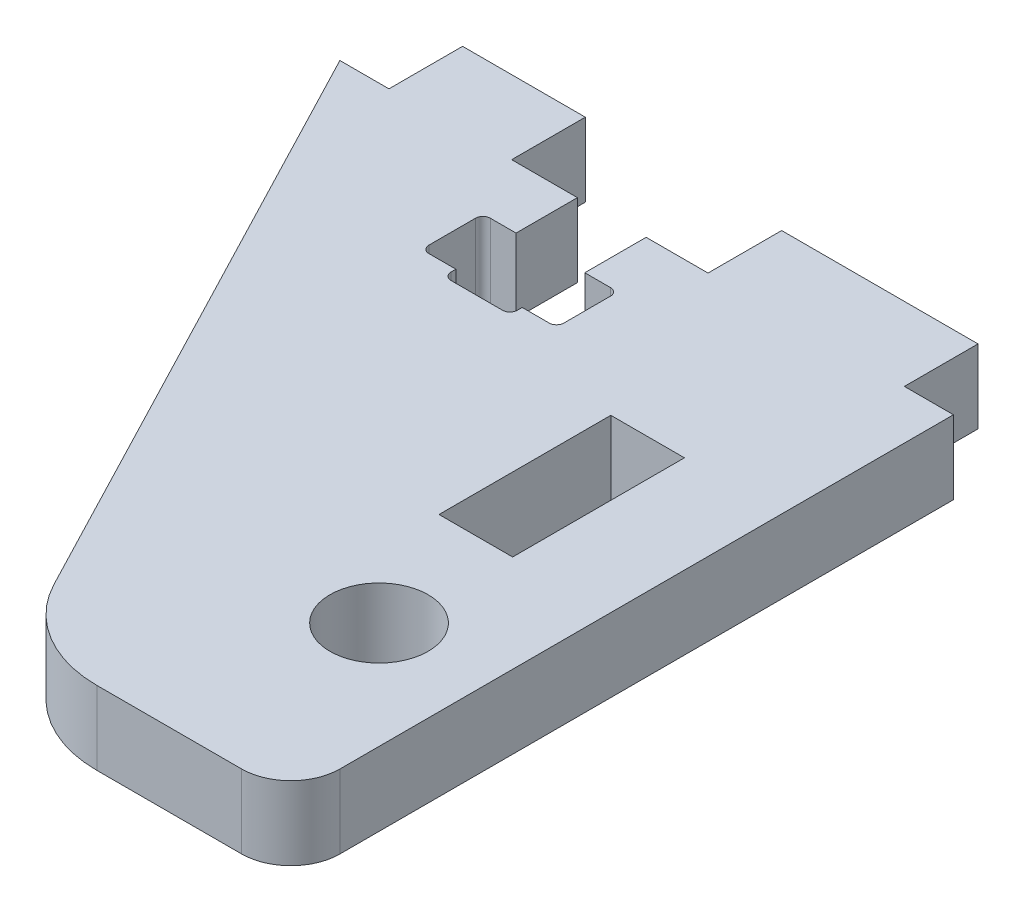
SolidWorks part; units mm, degrees
ref_plane "前视基准面" through (0, 0, 0) normal (0, 0, 1) x (1, 0, 0)
ref_plane "上视基准面" through (0, 0, 0) normal (0, 1, 0) x (1, 0, 0)
ref_plane "右视基准面" through (0, 0, 0) normal (1, 0, 0) x (0, 0, -1)
sketch "草图1" plane through (0, 0, 0) normal (0, 0, 1) x (1, 0, 0)
  line L0 (0, 0) -> (25, 0)
  line L4 (25, 0) -> (25, 5)
  line L5 (25, 5) -> (0, 5)
  line L6 (0, 5) -> (0, 0)
extrude "凸台-拉伸1" add sketch "草图1" along normal blind 24
sketch "草图2" plane through (0, 0, 0) normal (0, 0, -1) x (-1, 0, 0)
  line L0 (0, 5) -> (-2, 5)
  line L1 (-2, 5) -> (-2, 0)
  line L2 (-2, 5) -> (-7, 5)
  line L3 (-7, 5) -> (-7, 0)
  line L4 (0, 0) -> (0, 5)
  line L5 (0, 5) -> (-25, 5)
  line L6 (-25, 5) -> (-25, 0)
  line L7 (-25, 0) -> (0, 0)
  line L8 (0, 0) -> (0, 5)
  line L9 (0, 5) -> (-25, 5)
  line L10 (-25, 5) -> (-25, 0)
  line L11 (-25, 0) -> (0, 0)
  line L12 (-25, 5) -> (-23, 5)
  line L13 (-23, 5) -> (-23, 0)
  line L14 (-23, 5) -> (-15, 5)
  line L15 (-15, 5) -> (-15, 0)
  line M6 (0, 5) -> (-25, 5)
  line M8 (-25, 0) -> (0, 0)
  dimension "D1" = 0
extrude "凸台-拉伸2" add sketch "草图2" along normal blind 3 contours L3 L1 M6 M8 | L15 L9 L13 L11
sketch "草图3" plane through (0, 0, 0) normal (0, -1, 0) x (1, 0, 0)
  line L0 (0, 24) -> (25, 24) construction
  line L1 (0, 24) -> (25, 24)
  line L2 (0, 24) -> (0, 0) construction
  line L3 (0, 24) -> (0, 0)
  line L4 (0, 0) -> (12.5, 24)
  line M12 (0, 24) -> (0, 0)
extrude "切除-拉伸2" cut sketch "草图3" against normal blind 5 contours L4 L1 M12
sketch "草图4" plane through (0, 0, 0) normal (0, -1, 0) x (1, 0, 0)
  line L0 (12.5, 24) -> (25, 24) construction
  line L1 (12.5, 24) -> (25, 24)
  line L2 (25, 24) -> (25, 27)
  line L3 (25, 27) -> (14.0625, 27)
  line L4 (12.5, 24) -> (14.0625, 27)
extrude "凸台-拉伸3" add sketch "草图4" against normal up to surface (5 mm away) up to face at (13.0417, 5, 3)
fillet "圆角1" radius 5 1 edges at (14.0625, 2.5, 27)
fillet "圆角2" radius 2 1 edges at (25, 2.5, 27)
sketch "草图7" plane through (0, 5, 0) normal (0, 1, 0) x (1, 0, 0)
  line L12 (17.0959, -27) -> (23, -27)
  line L13 (25, -25) -> (25, 0)
  line L14 (25, 0) -> (23, 0)
  line L15 (23, 0) -> (23, 3)
  line L16 (23, 3) -> (15, 3)
  line L17 (15, 3) -> (15, 0)
  line L18 (15, 0) -> (7, 0)
  line L19 (7, 0) -> (7, 3)
  line L20 (7, 3) -> (2, 3)
  line L21 (2, 3) -> (2, 0)
  line L22 (2, 0) -> (0, 0)
  line L23 (0, 0) -> (12.6613, -24.3097)
  line L24 (17.0959, -27) -> (23, -27)
  line L25 (25, -25) -> (25, 0)
  line L26 (25, 0) -> (23, 0)
  line L27 (23, 0) -> (23, 3)
  line L28 (23, 3) -> (15, 3)
  line L29 (15, 3) -> (15, 0)
  line L30 (15, 0) -> (7, 0)
  line L31 (7, 0) -> (7, 3)
  line L32 (7, 3) -> (2, 3)
  line L33 (2, 3) -> (2, 0)
  line L34 (2, 0) -> (0, 0)
  line L35 (0, 0) -> (12.6613, -24.3097)
  arc A2 (23, -27) -> (25, -25) centre (23, -25) ccw
  arc A3 (12.6613, -24.3097) -> (17.0959, -27) centre (17.0959, -22) ccw
  arc A4 (23, -27) -> (25, -25) centre (23, -25) ccw
  arc A5 (12.6613, -24.3097) -> (17.0959, -27) centre (17.0959, -22) ccw
  dimension "D1" = 0
extrude "切除-拉伸4" cut sketch "草图7" against normal blind 2
extrude "切除-拉伸5" cut sketch "草图8" against normal blind 3
sketch "草图8" plane through (38.2212, 0, -111.6207) normal (0, -1, 0) x (0, 0, -1)
  line L1 (-114.1207, -28.543) -> (-111.6207, -28.543)
  line L3 (-111.6207, -25.743) -> (-114.1207, -25.743)
  line L5 (-114.1207, -25.743) -> (-114.1207, -24.693)
  line L7 (-114.4207, -24.393) -> (-116.3207, -24.393)
  line L9 (-116.6207, -24.693) -> (-116.6207, -25.793)
  line L11 (-116.6207, -25.793) -> (-116.8207, -25.793)
  line L13 (-117.1207, -26.093) -> (-117.1207, -28.193)
  line L15 (-116.8207, -28.493) -> (-116.6207, -28.493)
  line L17 (-116.6207, -28.493) -> (-116.6207, -29.593)
  line L19 (-116.3207, -29.893) -> (-114.4207, -29.893)
  line L21 (-114.1207, -29.593) -> (-114.1207, -28.543)
  line L22 (-111.6207, -28.543) -> (-111.6207, -25.743)
  arc A1 (-114.1207, -24.693) -> (-114.4207, -24.393) centre (-114.4207, -24.693) ccw
  arc A3 (-116.3207, -24.393) -> (-116.6207, -24.693) centre (-116.3207, -24.693) ccw
  arc A5 (-116.8207, -25.793) -> (-117.1207, -26.093) centre (-116.8207, -26.093) ccw
  arc A7 (-117.1207, -28.193) -> (-116.8207, -28.493) centre (-116.8207, -28.193) ccw
  arc A9 (-116.6207, -29.593) -> (-116.3207, -29.893) centre (-116.3207, -29.593) ccw
  arc A11 (-114.4207, -29.893) -> (-114.1207, -29.593) centre (-114.4207, -29.593) ccw
extrude "切除-拉伸6" cut sketch "草图9" against normal blind 3
sketch "草图9" plane through (38.2212, 0, -111.6207) normal (0, -1, 0) x (0, 0, -1)
  circle A1 centre (-130.6724, -17.5743) radius 2
extrude "切除-拉伸7" cut sketch "草图10" against normal blind 3
sketch "草图10" plane through (38.2212, 0, -111.6207) normal (0, -1, 0) x (0, 0, -1)
  line L8 (-125.6207, -17.1818) -> (-125.6207, -20.1818)
  line L9 (-125.6207, -20.1818) -> (-118.6207, -20.1818)
  line L10 (-118.6207, -20.1818) -> (-118.6207, -17.1818)
  line L11 (-118.6207, -17.1818) -> (-125.6207, -17.1818)
